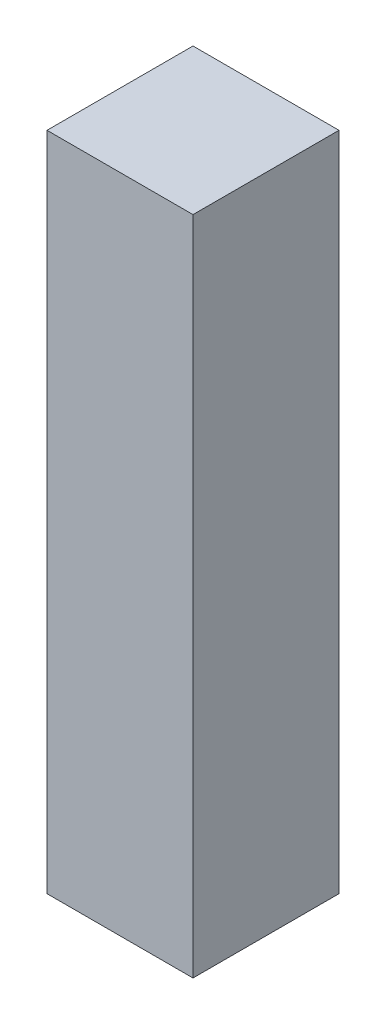
SolidWorks part; units mm, degrees
ref_plane "Front Plane" through (0, 0, 0) normal (0, 0, 1) x (1, 0, 0)
ref_plane "Top Plane" through (0, 0, 0) normal (0, 1, 0) x (1, 0, 0)
ref_plane "Right Plane" through (0, 0, 0) normal (1, 0, 0) x (0, 0, -1)
sketch "Sketch1" plane through (0, 0, 0) normal (0, 1, 0) x (1, 0, 0)
  line L1 (-1.325, -1.325) -> (1.325, -1.325)
  line L2 (-1.325, -1.325) -> (-1.325, 1.325)
  line L3 (-1.325, 1.325) -> (1.325, 1.325)
  line L4 (1.325, -1.325) -> (1.325, 1.325)
  line L5 (-1.325, -1.325) -> (1.325, 1.325) construction
  line L6 (-1.325, 1.325) -> (1.325, -1.325) construction
  point P0 (0, 0)
  dimension "D1" = 2.65
extrude "Boss-Extrude1" add sketch "Sketch1" along normal blind 12
